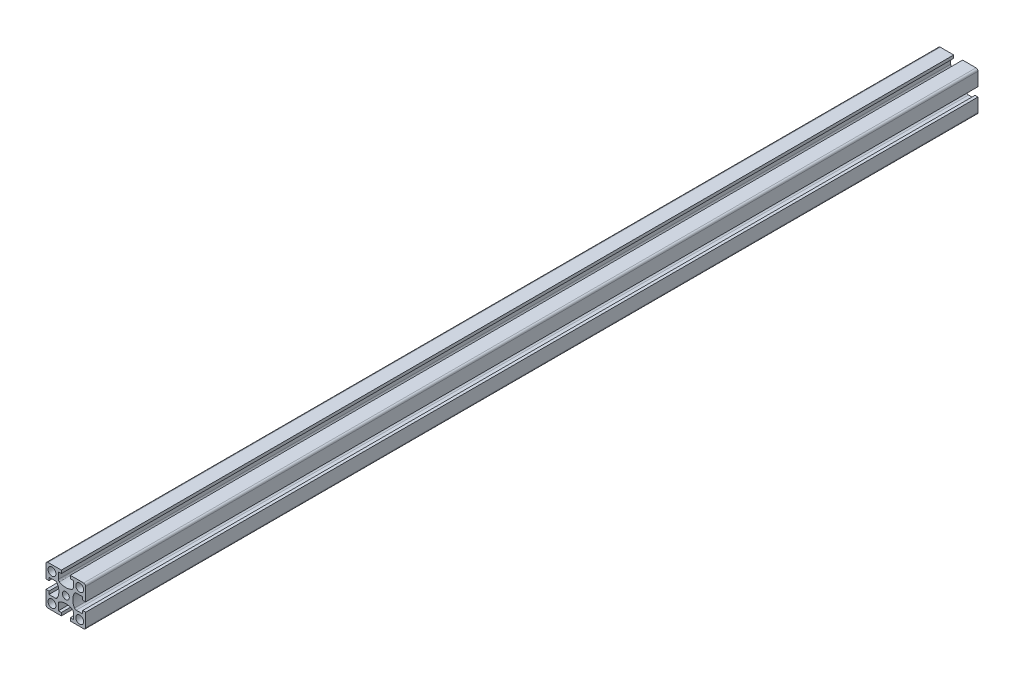
SolidWorks part; units mm, degrees
ref_plane "Front Plane" through (0, 0, 0) normal (0, 0, 1) x (1, 0, 0)
ref_plane "Top Plane" through (0, 0, 0) normal (0, 1, 0) x (1, 0, 0)
ref_plane "Right Plane" through (0, 0, 0) normal (1, 0, 0) x (0, 0, -1)
sketch "Sketch1" plane through (0, 0, 0) normal (0, 0, 1) x (1, 0, 0)
  line L64 (-10, 9) -> (-10, 2.25)
  line L65 (-10, 2.25) -> (-8.5, 2.25)
  line L66 (-8.5, 2.25) -> (-8.5, 3.75)
  line L67 (-8.5, 3.75) -> (-5.2369, 3.75)
  line L68 (-5.2369, -3.75) -> (-8.5, -3.75)
  line L69 (-8.5, -3.75) -> (-8.5, -2.25)
  line L70 (-8.5, -2.25) -> (-10, -2.25)
  line L71 (-10, -2.25) -> (-10, -9)
  line L72 (-9, -10) -> (-2.25, -10)
  line L73 (-2.25, -10) -> (-2.25, -8.5)
  line L74 (-2.25, -8.5) -> (-3.75, -8.5)
  line L75 (-3.75, -8.5) -> (-3.75, -5.2369)
  line L76 (3.75, -5.2369) -> (3.75, -8.5)
  line L77 (3.75, -8.5) -> (2.25, -8.5)
  line L78 (2.25, -8.5) -> (2.25, -10)
  line L79 (2.25, -10) -> (9, -10)
  line L80 (10, -9) -> (10, -2.25)
  line L81 (10, -2.25) -> (8.5, -2.25)
  line L82 (8.5, -2.25) -> (8.5, -3.75)
  line L83 (8.5, -3.75) -> (5.2369, -3.75)
  line L84 (5.2369, 3.75) -> (8.5, 3.75)
  line L85 (8.5, 3.75) -> (8.5, 2.25)
  line L86 (8.5, 2.25) -> (10, 2.25)
  line L87 (10, 2.25) -> (10, 9)
  line L88 (9, 10) -> (2.25, 10)
  line L89 (2.25, 10) -> (2.25, 8.5)
  line L90 (2.25, 8.5) -> (3.75, 8.5)
  line L91 (3.75, 8.5) -> (3.75, 5.2369)
  line L92 (-3.75, 5.2369) -> (-3.75, 8.5)
  line L93 (-3.75, 8.5) -> (-2.25, 8.5)
  line L94 (-2.25, 8.5) -> (-2.25, 10)
  line L95 (-2.25, 10) -> (-9, 10)
  circle A5 centre (-7, -7) radius 2
  circle A6 centre (7, -7) radius 2
  circle A7 centre (7, 7) radius 2
  circle A8 centre (0, 0) radius 1.75
  circle A9 centre (-7, 7) radius 2
  arc A32 (-9, 10) -> (-10, 9) centre (-9, 9) ccw
  arc A33 (-4.3708, 3.25) -> (-5.2369, 3.75) centre (-5.2369, 2.75) ccw
  arc A34 (-4.3708, -3.25) -> (-4.3708, 3.25) centre (-10, 0) ccw
  arc A35 (-5.2369, -3.75) -> (-4.3708, -3.25) centre (-5.2369, -2.75) ccw
  arc A36 (-10, -9) -> (-9, -10) centre (-9, -9) ccw
  arc A37 (-3.25, -4.3708) -> (-3.75, -5.2369) centre (-2.75, -5.2369) ccw
  arc A38 (3.25, -4.3708) -> (-3.25, -4.3708) centre (0, -10) ccw
  arc A39 (3.75, -5.2369) -> (3.25, -4.3708) centre (2.75, -5.2369) ccw
  arc A40 (9, -10) -> (10, -9) centre (9, -9) ccw
  arc A41 (4.3708, -3.25) -> (5.2369, -3.75) centre (5.2369, -2.75) ccw
  arc A42 (4.3708, 3.25) -> (4.3708, -3.25) centre (10, 0) ccw
  arc A43 (5.2369, 3.75) -> (4.3708, 3.25) centre (5.2369, 2.75) ccw
  arc A44 (10, 9) -> (9, 10) centre (9, 9) ccw
  arc A45 (3.25, 4.3708) -> (3.75, 5.2369) centre (2.75, 5.2369) ccw
  arc A46 (-3.25, 4.3708) -> (3.25, 4.3708) centre (0, 10) ccw
  arc A47 (-3.75, 5.2369) -> (-3.25, 4.3708) centre (-2.75, 5.2369) ccw
extrude "Boss-Extrude1" add sketch "Sketch1" along normal blind 450
